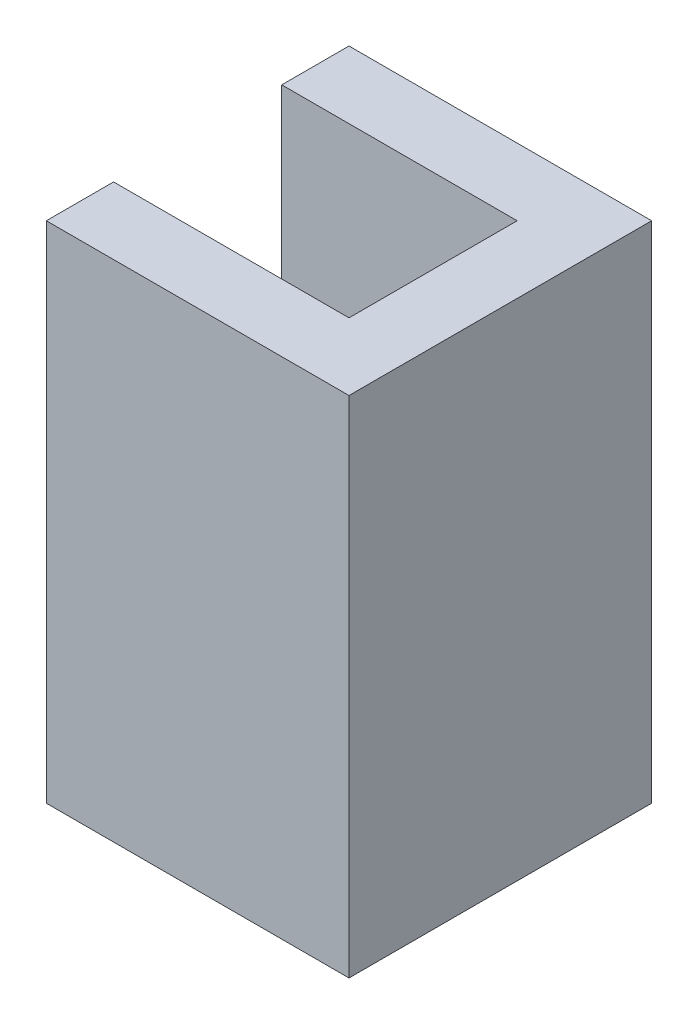
SolidWorks part; units mm, degrees
ref_plane "Front Plane" through (0, 0, 0) normal (0, 0, 1) x (1, 0, 0)
ref_plane "Top Plane" through (0, 0, 0) normal (0, 1, 0) x (1, 0, 0)
ref_plane "Right Plane" through (0, 0, 0) normal (1, 0, 0) x (0, 0, -1)
sketch "Sketch1" plane through (0, 0, 0) normal (0, 1, 0) x (1, 0, 0)
  line L1 (-4.5, -4.5) -> (4.5, -4.5)
  line L2 (-4.5, -4.5) -> (-4.5, 4.5)
  line L3 (-4.5, 4.5) -> (4.5, 4.5)
  line L4 (4.5, -4.5) -> (4.5, 4.5)
  line L5 (-4.5, -4.5) -> (4.5, 4.5) construction
  line L6 (-4.5, 4.5) -> (4.5, -4.5) construction
  line L7 (-2.5, -2.5) -> (2.5, -2.5)
  line L8 (-2.5, -2.5) -> (-2.5, 2.5)
  line L9 (-2.5, 2.5) -> (2.5, 2.5)
  line L10 (2.5, -2.5) -> (2.5, 2.5)
  line L11 (-2.5, -2.5) -> (2.5, 2.5) construction
  line L12 (-2.5, 2.5) -> (2.5, -2.5) construction
  circle A0 centre (0, 0) radius 7 construction
  dimension "D1" = 14
  dimension "D2" = 9
  dimension "D3" = 9
  dimension "D4" = 5
  dimension "D5" = 5
extrude "Boss-Extrude1" add sketch "Sketch1" along normal blind 15
sketch "Sketch2" plane through (0, 15, 0) normal (0, 1, 0) x (1, 0, 0)
  line L0 (-2.5, 2.5) -> (-4.5, 2.5)
  line L1 (-4.5, 4.5) -> (-4.5, -4.5) construction
  line L2 (-2.5, -2.5) -> (-4.5, -2.5)
  line L3 (-4.5, 2.5) -> (-4.5, -2.5)
  line L4 (-2.5, 2.5) -> (-2.5, -2.5)
extrude "Cut-Extrude1" cut sketch "Sketch2" against normal through all
